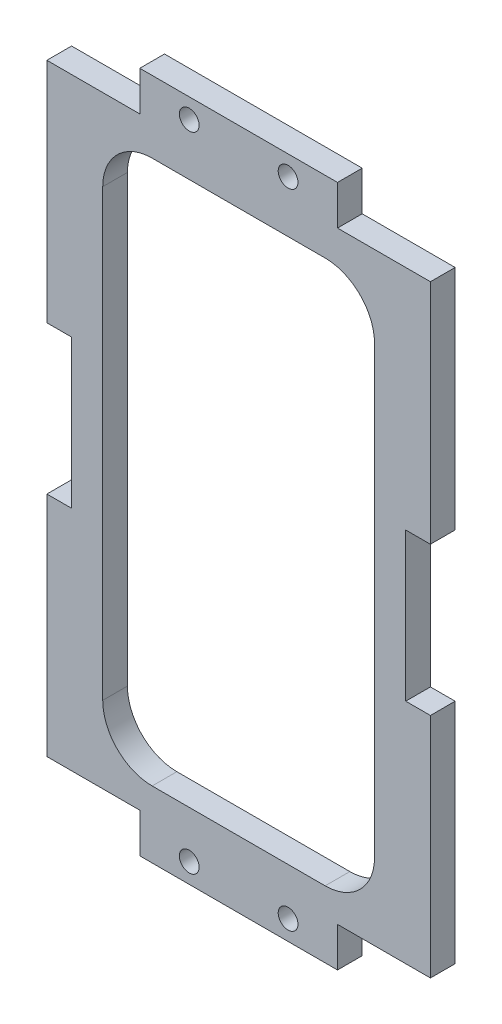
SolidWorks part; units mm, degrees
ref_plane "前视基准面" through (0, 0, 0) normal (0, 0, 1) x (1, 0, 0)
ref_plane "上视基准面" through (0, 0, 0) normal (0, 1, 0) x (1, 0, 0)
ref_plane "右视基准面" through (0, 0, 0) normal (1, 0, 0) x (0, 0, -1)
sketch "草图1" plane through (0, 0, 0) normal (0, 0, 1) x (1, 0, 0)
  line L1 (0, 0) -> (77.6, 0)
  line L2 (0, 0) -> (0, 137)
  line L3 (0, 137) -> (77.6, 137)
  line L4 (77.6, 0) -> (77.6, 137)
  dimension "D1" = 77.6
  dimension "D2" = 137
extrude "凸台-拉伸1" add sketch "草图1" along normal blind 5
sketch "草图3" plane through (0, 0, 5) normal (0, 0, 1) x (1, 0, 0)
  line L0 (77.6, 0) -> (77.6, 137) construction
  line L1 (77.6, 83.5) -> (72.6, 83.5)
  line L2 (77.6, 83.5) -> (77.6, 53.5)
  line L3 (77.6, 53.5) -> (72.6, 53.5)
  line L4 (72.6, 83.5) -> (72.6, 53.5)
  line L5 (0, 137) -> (0, 0) construction
  line L6 (0, 83.5) -> (5, 83.5)
  line L7 (0, 83.5) -> (0, 53.5)
  line L8 (0, 53.5) -> (5, 53.5)
  line L9 (5, 83.5) -> (5, 53.5)
  line L12 (0, 0) -> (18.8, 0)
  line L13 (0, 0) -> (0, 7.5)
  line L14 (0, 7.5) -> (18.8, 7.5)
  line L15 (77.6, 137) -> (0, 137) construction
  line L16 (18.8, 0) -> (18.8, 7.5)
  line L17 (18.8, 137) -> (18.8, 129.5)
  line L18 (77.6, 0) -> (58.8, 0)
  line L19 (58.8, 137) -> (58.8, 129.5)
  line L20 (18.8, 129.5) -> (0, 129.5)
  line L21 (0, 129.5) -> (0, 137)
  line L22 (0, 137) -> (18.8, 137)
  line L23 (58.8, 129.5) -> (77.6, 129.5)
  line L24 (77.6, 129.5) -> (77.6, 137)
  line L25 (77.6, 137) -> (58.8, 137)
  line L26 (58.8, 137) -> (58.766, 136.6742)
  line L27 (77.6, 0) -> (77.6, 7.5)
  line L28 (77.6, 7.5) -> (58.8, 7.5)
  line L29 (58.8, 0) -> (58.8, 7.5)
  line M16 (0, 137) -> (0, 0)
  line M17 (0, 0) -> (77.6, 0)
  line M18 (77.6, 0) -> (77.6, 137)
  line M19 (77.6, 137) -> (0, 137)
  dimension "D1" = 18.8
  dimension "D2" = 5
  dimension "D3" = 5
  dimension "D4" = 30
  dimension "D5" = 30
  dimension "D6" = 53.5
  dimension "D7" = 53.5
  dimension "D8" = 40
  dimension "D9" = 18.8
  dimension "D10" = 7.5
  dimension "D11" = 7.5
  dimension "D12" = 7.5
  dimension "D13" = 18.8
  dimension "D14" = 18.8
extrude "切除-拉伸1" cut sketch "草图3" against normal blind 5 contours L20 L17 M19 M16 | L16 L14 M17 M16 | L29 L28 M17 M18 | L19 L23 M18 M19 | L1 L4 L3 M18 | L9 L6 L8 M16
sketch "草图4" plane through (0, 0, 5) normal (0, 0, 1) x (1, 0, 0)
  line L0 (58.8, 137) -> (18.8, 137) construction
  line L1 (18.8, 0) -> (58.8, 0) construction
  line L2 (18.8, 137) -> (18.8, 129.5) construction
  line L3 (18.8, 0) -> (18.8, 7.5) construction
  circle A0 centre (28.8, 133.5) radius 2
  circle A1 centre (48.8, 133.5) radius 2
  circle A2 centre (28.8, 3.5) radius 2
  circle A3 centre (48.8, 3.5) radius 2
  dimension "D1" = 4
  dimension "D2" = 4
  dimension "D3" = 4
  dimension "D4" = 4
  dimension "D5" = 3.5
  dimension "D6" = 20
  dimension "D7" = 20
  dimension "D8" = 3.5
  dimension "D9" = 10
  dimension "D10" = 10
extrude "切除-拉伸2" cut sketch "草图4" against normal blind 5
sketch "草图5" plane through (0, 0, 0) normal (0, 0, -1) x (-1, 0, 0)
  line L1 (-66.3, 123) -> (-11.3, 123)
  line L2 (-66.3, 123) -> (-66.3, 13)
  line L3 (-66.3, 13) -> (-11.3, 13)
  line L4 (-11.3, 123) -> (-11.3, 13)
  line L5 (-72.6, 83.5) -> (-72.6, 53.5) construction
  line L8 (-18.8, 129.5) -> (0, 129.5) construction
  dimension "D1" = 55
  dimension "D2" = 6.3
  dimension "D3" = 110
  dimension "D4" = 6.5
extrude "切除-拉伸3" cut sketch "草图5" against normal blind 7
fillet "圆角1" radius 10 4 edges at (66.3, 123, 2.5) (66.3, 13, 2.5) (11.3, 13, 2.5) (11.3, 123, 2.5)
sketch "草图7" plane through (0, 0, 5) normal (0, 0, 1) x (1, 0, 0)
  line L1 (18.8, 137) -> (58.8, 137)
  line L2 (18.8, 137) -> (18.8, 137.5)
  line L3 (18.8, 137.5) -> (58.8, 137.5)
  line L4 (58.8, 137) -> (58.8, 137.5)
  line L5 (18.8, 0) -> (58.8, 0)
  line L6 (18.8, 0) -> (18.8, -0.5)
  line L7 (18.8, -0.5) -> (58.8, -0.5)
  line L8 (58.8, 0) -> (58.8, -0.5)
  dimension "D1" = 0.5
  dimension "D2" = 0.5
extrude "凸台-拉伸2" add sketch "草图7" against normal blind 5
